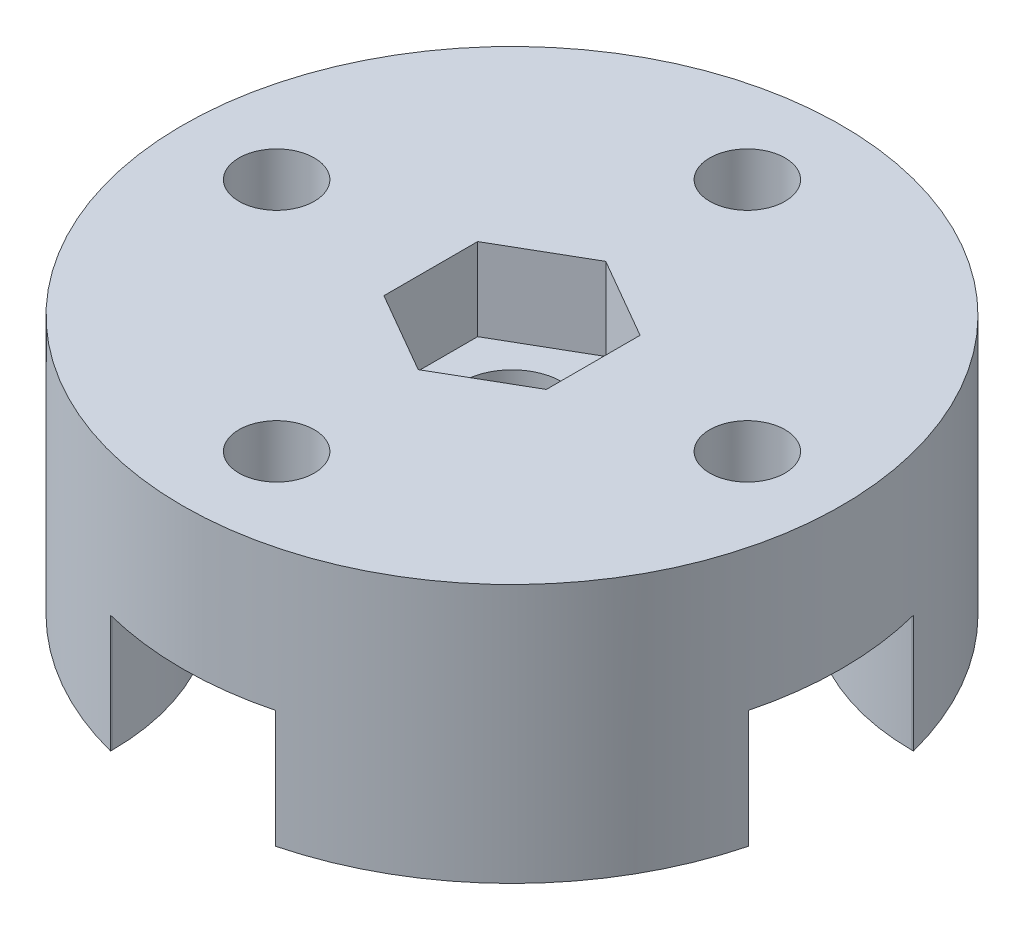
SolidWorks part; units mm, degrees
ref_plane "Front Plane" through (0, 0, 0) normal (0, 0, 1) x (1, 0, 0)
ref_plane "Top Plane" through (0, 0, 0) normal (0, 1, 0) x (1, 0, 0)
ref_plane "Right Plane" through (0, 0, 0) normal (1, 0, 0) x (0, 0, -1)
sketch "Sketch1" plane through (0, 0, 0) normal (0, 1, 0) x (1, 0, 0)
  line L1 (0, 3.9837) -> (-3.45, 1.9919)
  line L2 (-3.45, 1.9919) -> (-3.45, -1.9919)
  line L3 (-3.45, -1.9919) -> (0, -3.9837)
  line L4 (0, -3.9837) -> (3.45, -1.9919)
  line L5 (3.45, -1.9919) -> (3.45, 1.9919)
  line L6 (3.45, 1.9919) -> (0, 3.9837)
  circle A0 centre (0, 0) radius 10 construction
  circle A1 centre (0, 10) radius 1.6
  circle A2 centre (10, 0) radius 1.6
  circle A3 centre (0, -10) radius 1.6
  circle A4 centre (-10, 0) radius 1.6
  circle A5 centre (0, 0) radius 14
  circle A6 centre (0, 0) radius 3.45 construction
  dimension "D1" = 20
  dimension "D2" = 3.2
  dimension "D4" = 28
  dimension "D5" = 6.9
  dimension "D3" = 4
extrude "Boss-Extrude1" add sketch "Sketch1" along normal blind 3.5
sketch "Sketch2" plane through (0, 0, 0) normal (0, -1, 0) x (1, 0, 0)
  circle A0 centre (0, 0) radius 2.125
  circle A1 centre (10, 0) radius 1.6 construction
  circle A2 centre (0, -10) radius 1.6 construction
  circle A3 centre (-10, 0) radius 1.6 construction
  circle A4 centre (0, 10) radius 1.6 construction
  circle A5 centre (0, 0) radius 14 construction
  circle A6 centre (10, 0) radius 1.6
  circle A7 centre (0, -10) radius 1.6
  circle A8 centre (-10, 0) radius 1.6
  circle A9 centre (0, 10) radius 1.6
  circle A10 centre (0, 0) radius 14
  dimension "D1" = 4.25
extrude "Boss-Extrude2" add sketch "Sketch2" along normal blind 2.5
chamfer "Chamfer1" distance 1.5 angle 45 5 edges at (0, -2.5, -2.125) (0, -2.5, -11.6) (10, -2.5, -1.6) (-10, -2.5, -1.6) (0, -2.5, 8.4)
sketch "Sketch3" plane through (0, -2.5, 0) normal (0, -1, 0) x (1, 0, 0)
  line L2 (4, -3.5) -> (3.5, -3.5)
  line L3 (4, 3.5) -> (3.5, 3.5)
  line L5 (-3.5, -4) -> (-3.5, -3.5)
  line L6 (3.5, -4) -> (3.5, -3.5)
  line L8 (-4, 3.5) -> (-3.5, 3.5)
  line L9 (-4, -3.5) -> (-3.5, -3.5)
  line L11 (3.5, 4) -> (3.5, 3.5)
  line L12 (-3.5, 4) -> (-3.5, 3.5)
  line L13 (-3.5, -3.5) -> (-3.5, -13.5554)
  line L14 (3.5, 3.5) -> (13.5554, 3.5)
  line L15 (-3.5, 3.5) -> (-13.5554, 3.5)
  line L17 (3.5, 3.5) -> (3.5, 13.5554)
  line L18 (3.5, -3.5) -> (3.5, -13.5554)
  line L19 (-3.5, 3.5) -> (-3.5, 13.5554)
  line L21 (-3.5, -3.5) -> (-13.5554, -3.5)
  line L22 (3.5, -3.5) -> (13.5554, -3.5)
  circle A0 centre (0, 0) radius 14 construction
  arc A1 (-13.5554, -3.5) -> (-3.5, -13.5554) centre (0, 0) ccw
  arc A10 (-3.5, 13.5554) -> (-13.5554, 3.5) centre (0, 0) ccw
  arc A11 (13.5554, 3.5) -> (3.5, 13.5554) centre (0, 0) ccw
  arc A12 (3.5, -13.5554) -> (13.5554, -3.5) centre (0, 0) ccw
  point P7 (-2, 0)
  circle M14 centre (0, 0) radius 14
  dimension "D2" = 10.0554
  dimension "D1" = 10.0554
  dimension "D3" = 3.5
  dimension "D4" = 3.5
extrude "Boss-Extrude3" add sketch "Sketch3" along normal blind 5 contours L12 L19 L15 L8 M14 | L17 L11 L3 L14 M14 | L22 L2 L6 L18 M14 | L9 L21 L13 L5 M14
fillet "Fillet1" radius 10 4 edges at (-3.5, -5, -3.5) (3.5, -5, -3.5) (3.5, -5, 3.5) (-3.5, -5, 3.5)
